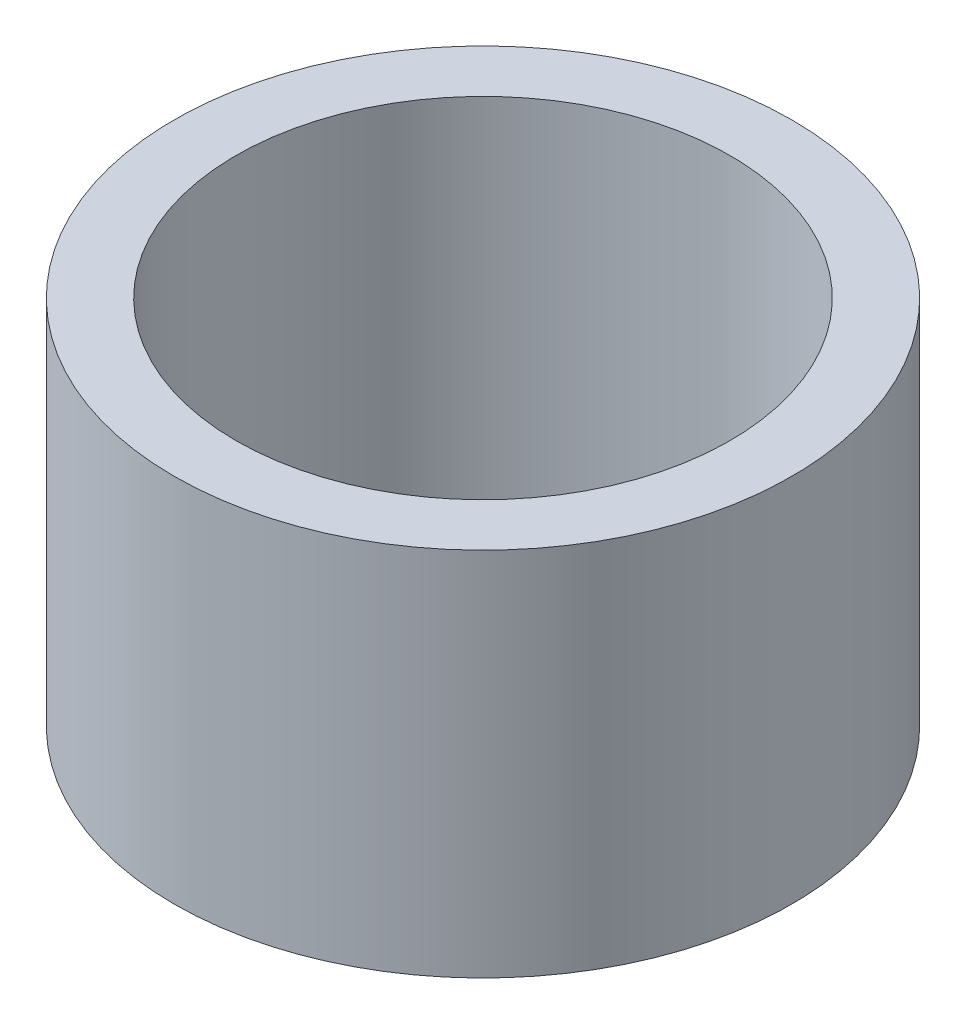
SolidWorks part; units mm, degrees
material "1060 Alloy"
ref_plane "Front Plane" through (0, 0, 0) normal (0, 0, 1) x (1, 0, 0)
ref_plane "Top Plane" through (0, 0, 0) normal (0, 1, 0) x (1, 0, 0)
ref_plane "Right Plane" through (0, 0, 0) normal (1, 0, 0) x (0, 0, -1)
sketch "Sketch1" plane through (0, 0, 0) normal (0, 1, 0) x (1, 0, 0)
  circle A0 centre (0, 0) radius 5
  circle A1 centre (0, 0) radius 4
  dimension "D1" = 10
  dimension "D2" = 8
extrude "Boss-Extrude1" add sketch "Sketch1" along normal blind 6
